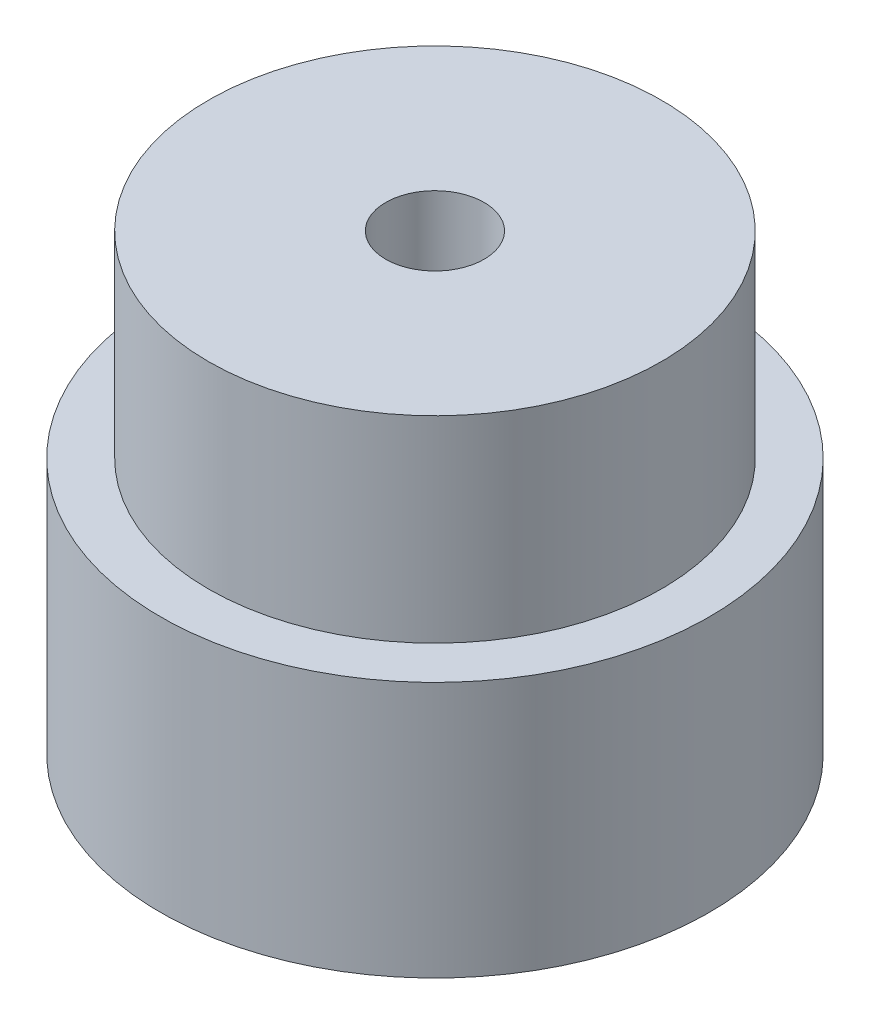
SolidWorks part; units mm, degrees
ref_plane "前视基准面" through (0, 0, 0) normal (0, 0, 1) x (1, 0, 0)
ref_plane "上视基准面" through (0, 0, 0) normal (0, 1, 0) x (1, 0, 0)
ref_plane "右视基准面" through (0, 0, 0) normal (1, 0, 0) x (0, 0, -1)
other "Configuration Table"
sketch "草图1" plane through (0, 0, 0) normal (0, 1, 0) x (1, 0, 0)
  circle A0 centre (0, 0) radius 13.94
extrude "凸台-拉伸1" add sketch "草图1" along normal blind 13
sketch "草图2" plane through (0, 13, 0) normal (0, 1, 0) x (1, 0, 0)
  circle A0 centre (0, 0) radius 11.5
extrude "凸台-拉伸2" add sketch "草图2" along normal blind 10
sketch "草图3" plane through (0, 23, 0) normal (0, 1, 0) x (1, 0, 0)
  circle A0 centre (0, 0) radius 2.5
extrude "切除-拉伸1" cut sketch "草图3" against normal blind 30
